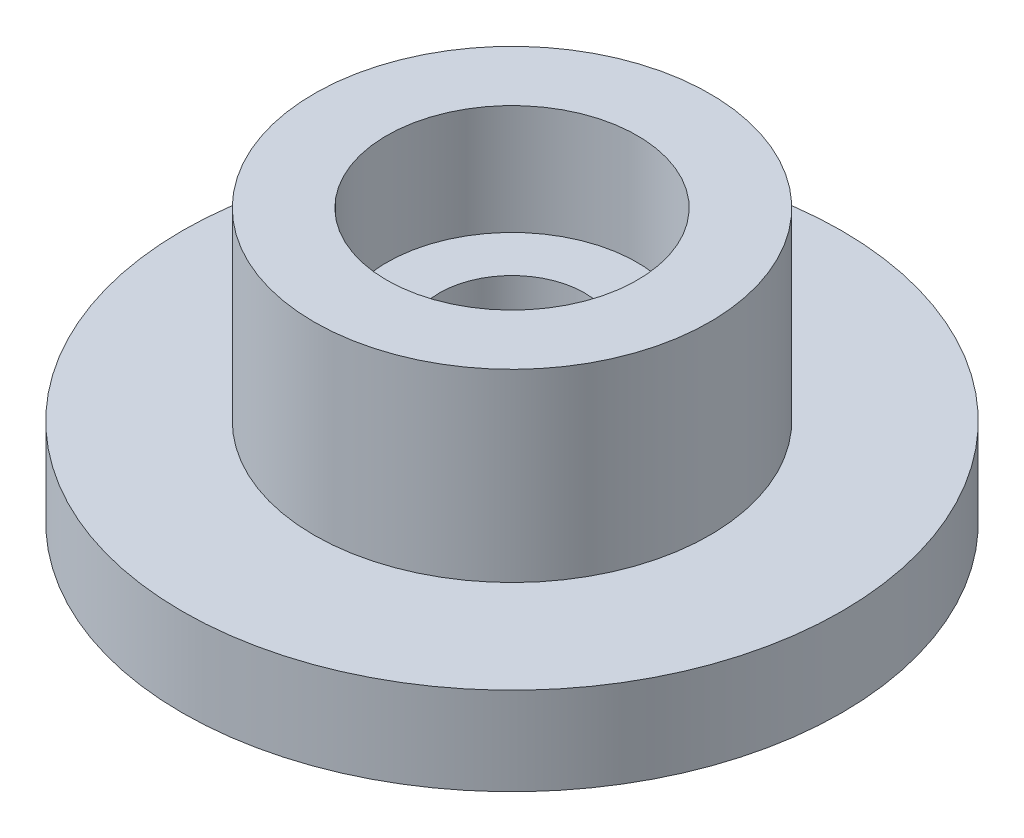
SolidWorks part; units mm, degrees
ref_plane "前视基准面" through (0, 0, 0) normal (0, 0, 1) x (1, 0, 0)
ref_plane "上视基准面" through (0, 0, 0) normal (0, 1, 0) x (1, 0, 0)
ref_plane "右视基准面" through (0, 0, 0) normal (1, 0, 0) x (0, 0, -1)
sketch "草图1" plane through (0, 0, 0) normal (0, 1, 0) x (1, 0, 0)
  circle A0 centre (0, 0) radius 7.5
  dimension "D1" = 15
extrude "凸台-拉伸1" add sketch "草图1" along normal blind 2
sketch "草图4" plane through (0, 2, 0) normal (0, 1, 0) x (1, 0, 0)
  circle A0 centre (0, 0) radius 2.85
  circle A1 centre (0, 0) radius 4.5
  dimension "D1" = 5.7
  dimension "D2" = 9
extrude "凸台-拉伸2" add sketch "草图4" along normal blind 4.2
sketch "草图5" plane through (0, 2, 0) normal (0, 1, 0) x (1, 0, 0)
  circle A0 centre (0, 0) radius 2.85
extrude "凸台-拉伸3" add sketch "草图5" along normal blind 1.7
sketch "草图6" plane through (0, 0, 0) normal (0, -1, 0) x (1, 0, 0)
  circle A0 centre (0, 0) radius 1.65
  dimension "D1" = 3.3
extrude "切除-拉伸1" cut sketch "草图6" against normal through all
